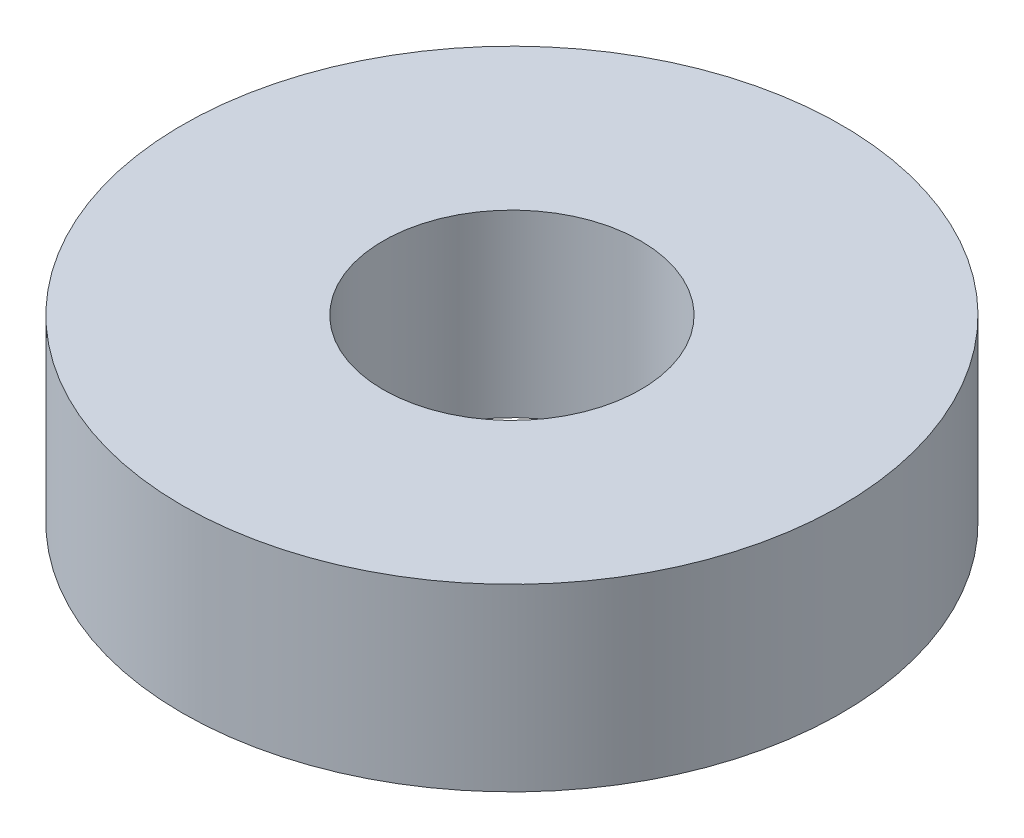
SolidWorks part; units mm, degrees
material "Onyx w/ CF"
ref_plane "Front Plane" through (0, 0, 0) normal (0, 0, 1) x (1, 0, 0)
ref_plane "Top Plane" through (0, 0, 0) normal (0, 1, 0) x (1, 0, 0)
ref_plane "Right Plane" through (0, 0, 0) normal (1, 0, 0) x (0, 0, -1)
sketch "Sketch1" plane through (0, 0, 0) normal (0, 1, 0) x (1, 0, 0)
  circle A0 centre (0, 0) radius 5.5
  dimension "D1" = 11
extrude "Boss-Extrude1" add sketch "Sketch1" along normal blind 3
hole_wizard "M4 Clearance Hole1" positions "Sketch2" profile "Sketch3" hole size "M4" standard "ANSI Metric" end condition up to next
sketch "Sketch2" plane through (0, 3, 0) normal (0, 1, 0) x (1, 0, 0)
  point P0 (0, 0)
sketch "Sketch3" plane through (0, 3, 0) normal (1, 0, 0) x (0, 0, 1)
  line L0 (0, 0) -> (0, 3)
  line L1 (0, 3) -> (2.15, 3)
  line L2 (2.15, 3) -> (2.15, 0)
  line L5 (2.15, 0) -> (0, 0)
  line L11 (0, -6.35) -> (0, 107.95) construction
  dimension "Thru Hole Dia." = 4.3
  dimension "Thru Hole Depth" = 3
sketch "Sketch5" plane through (0, 0, 0) normal (0, -1, 0) x (1, 0, 0)
  line L0 (2.7003, 4.677) -> (-2.7003, 4.677) construction
  line L1 (2.6269, -4.55) -> (5.2539, 0) construction
  line L2 (5.2539, 0) -> (2.6269, 4.55) construction
  line L3 (2.6269, 4.55) -> (-2.6269, 4.55) construction
  line L4 (-2.6269, 4.55) -> (-5.2539, 0) construction
  line L5 (-5.2539, 0) -> (-2.6269, -4.55) construction
  line L6 (-2.6269, -4.55) -> (2.6269, -4.55) construction
  line L7 (-2.7003, 4.677) -> (-5.4005, 0) construction
  line L8 (-5.4005, 0) -> (-2.7003, -4.677) construction
  line L9 (-2.7003, -4.677) -> (2.7003, -4.677) construction
  line L10 (2.7003, -4.677) -> (5.4005, 0) construction
  line L11 (5.4005, 0) -> (2.7003, 4.677) construction
  line L12 (1.9763, 3.423) -> (-1.9763, 3.423) construction
  line L13 (-1.9763, 3.423) -> (-3.9525, 0) construction
  line L14 (-3.9525, 0) -> (-1.9763, -3.423) construction
  line L15 (-1.9763, -3.423) -> (1.9763, -3.423) construction
  line L16 (1.9763, -3.423) -> (3.9525, 0) construction
  line L17 (3.9525, 0) -> (1.9763, 3.423) construction
  line L18 (-2.7003, 4.677) -> (-2.7003, 3.423) construction
  line L19 (-2.7003, 3.423) -> (2.7003, 3.423) construction
  line L20 (2.7003, 3.423) -> (2.7003, 4.677) construction
  line L21 (-3.9525, 0) -> (3.9525, 0) construction
  line L22 (-2.7003, -4.677) -> (2.7003, -4.677) construction
  line L23 (-2.7003, -4.677) -> (-2.7003, -3.423) construction
  line L24 (-2.7003, -3.423) -> (2.7003, -3.423) construction
  line L25 (2.7003, -4.677) -> (2.7003, -3.423) construction
  line L26 (-1.627, 3.423) -> (1.627, 3.423)
  line L27 (-1.627, 3.423) -> (-1.627, 4.677)
  line L28 (-1.627, 4.677) -> (1.627, 4.677)
  line L29 (1.627, 3.423) -> (1.627, 4.677)
  line L30 (-1.627, -4.677) -> (1.627, -4.677)
  line L31 (1.627, -3.423) -> (1.627, -4.677)
  line L32 (-1.627, -3.423) -> (1.627, -3.423)
  line L33 (-1.627, -3.423) -> (-1.627, -4.677)
  circle A0 centre (0, 0) radius 4.55 construction
  point P1 (0, 4.55)
  point P31 (0, 3.423)
  dimension "D1" = 9.1
  dimension "D4" = 3.254
  dimension "D2" = 0.127
  dimension "D3" = 1.254
extrude "Cut-Extrude2" cut sketch "Sketch5" against normal blind 2 contours L9 L25 L24 L23 | L19 L20 L0 L18 | L26 L29 L28 L27 | L32 L33 L30 L31
